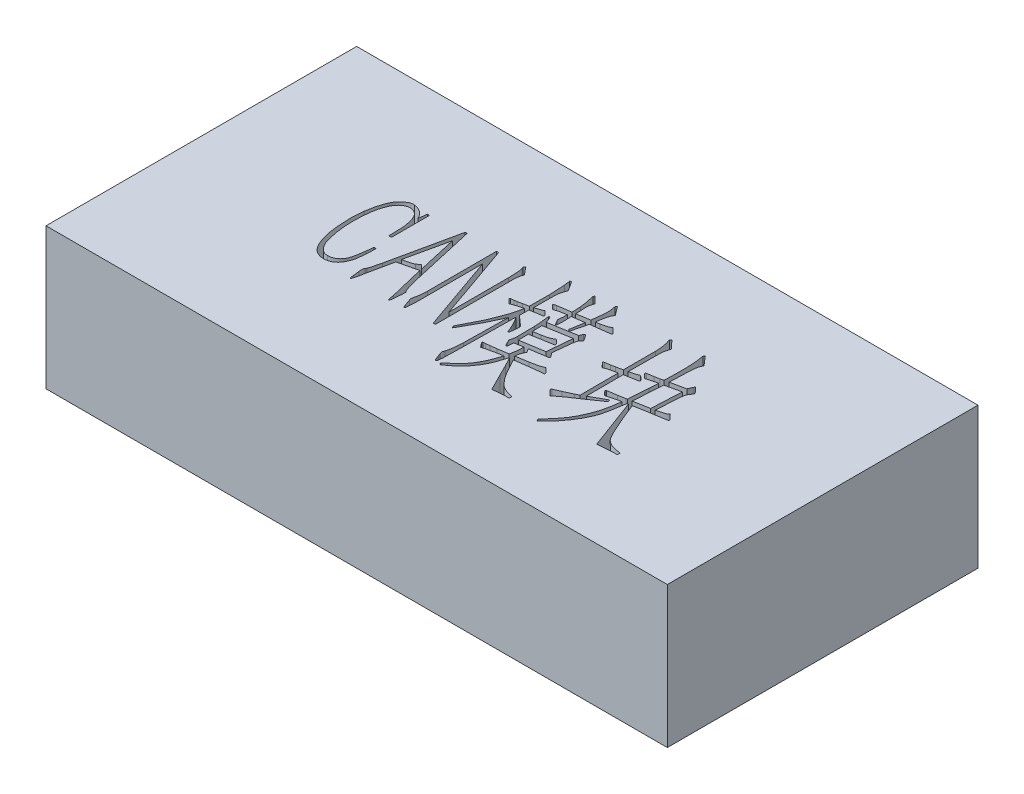
SolidWorks part; units mm, degrees
ref_plane "前视基准面" through (0, 0, 0) normal (0, 0, 1) x (1, 0, 0)
ref_plane "上视基准面" through (0, 0, 0) normal (0, 1, 0) x (1, 0, 0)
ref_plane "右视基准面" through (0, 0, 0) normal (1, 0, 0) x (0, 0, -1)
sketch "草图1" plane through (0, 0, 0) normal (0, 1, 0) x (1, 0, 0)
  line L1 (-11, 5.5) -> (11, 5.5)
  line L2 (-11, 5.5) -> (-11, -5.5)
  line L3 (-11, -5.5) -> (11, -5.5)
  line L4 (11, 5.5) -> (11, -5.5)
  line L5 (-11, 5.5) -> (11, -5.5) construction
  line L6 (-11, -5.5) -> (11, 5.5) construction
  point P0 (0, 0)
extrude "凸台-拉伸1" add sketch "草图1" along normal blind 5
sketch "草图2" plane through (0, 5, 0) normal (0, 1, 0) x (1, 0, 0)
  text T0 "CAN模块"
extrude "切除-拉伸1" cut sketch "草图2" against normal blind 2
